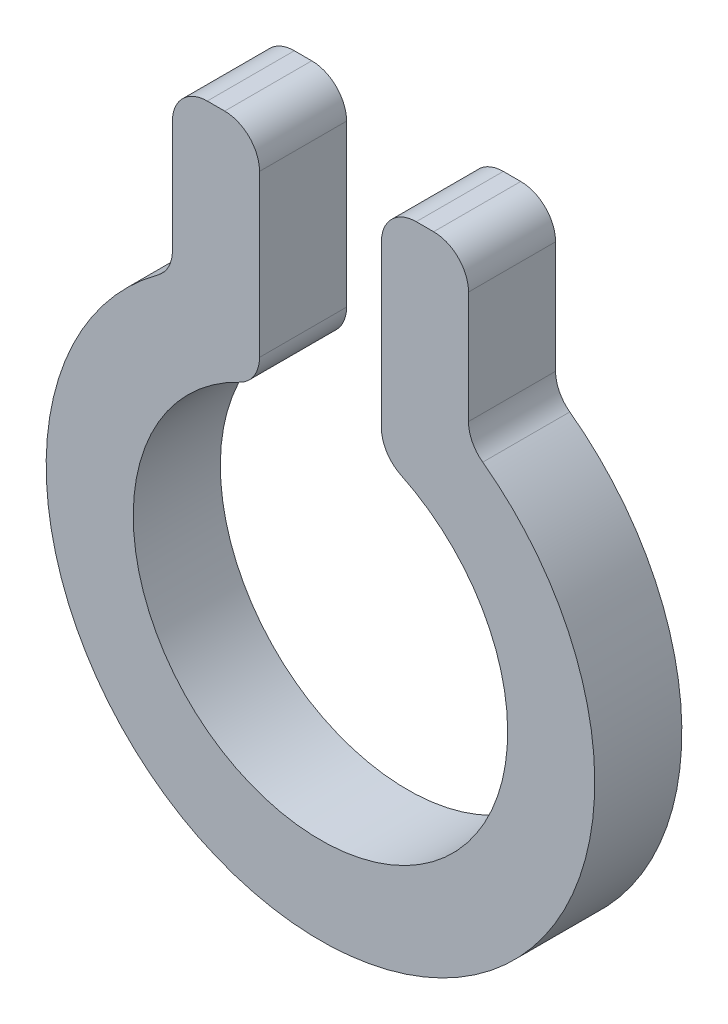
SolidWorks part; units mm, degrees
ref_plane "Front Plane" through (0, 0, 0) normal (0, 0, 1) x (1, 0, 0)
ref_plane "Top Plane" through (0, 0, 0) normal (0, 1, 0) x (1, 0, 0)
ref_plane "Right Plane" through (0, 0, 0) normal (1, 0, 0) x (0, 0, -1)
sketch "Sketch1" plane through (0, 0, 0) normal (0, 0, 1) x (1, 0, 0)
  line L0 (3.5, 22.75) -> (8.5, 22.75)
  line L2 (-3.5, 10.1643) -> (-3.5, 22.75)
  line L4 (3.5, 10.1643) -> (3.5, 22.75)
  line L5 (0, 0) -> (0, 8.507) construction
  line L8 (-8.5, 13.2594) -> (-8.5, 22.75)
  line L9 (-8.5, 22.75) -> (-3.5, 22.75)
  line L10 (8.5, 13.2594) -> (8.5, 22.75)
  arc A0 (-3.5, 10.1643) -> (3.5, 10.1643) centre (0, 0) ccw
  arc A1 (-8.5, 13.2594) -> (8.5, 13.2594) centre (0, 0) ccw
  point P4 (0, 15.75)
  point P9 (0, 15.75)
  dimension "D1" = 21.5
  dimension "D2" = 7
  dimension "D5" = 31.5
  dimension "D3" = 17
extrude "Boss-Extrude1" add sketch "Sketch1" along normal blind 5
fillet "Fillet1" radius 2 8 edges at (8.5, 13.2594, 2.5) (8.5, 22.75, 2.5) (3.5, 22.75, 2.5) (-3.5, 22.75, 2.5) (-8.5, 22.75, 2.5) (-8.5, 13.2594, 2.5) (3.5, 10.1643, 2.5) (-3.5, 10.1643, 2.5)
